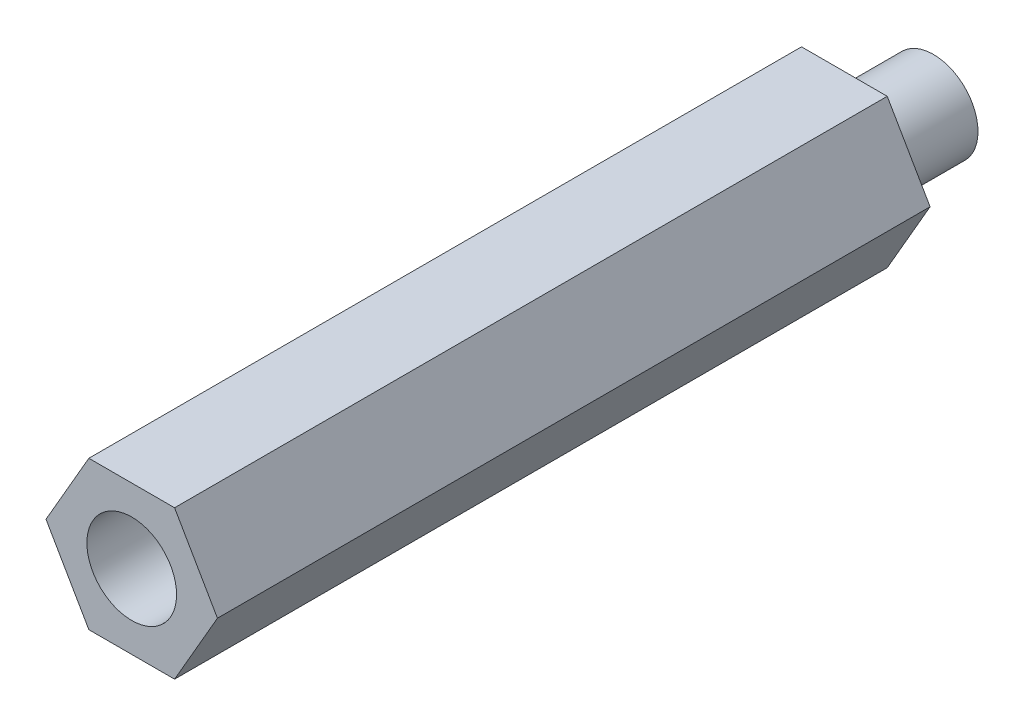
SolidWorks part; units mm, degrees
ref_plane "前视基准面" through (0, 0, 0) normal (0, 0, 1) x (1, 0, 0)
ref_plane "上视基准面" through (0, 0, 0) normal (0, 1, 0) x (1, 0, 0)
ref_plane "右视基准面" through (0, 0, 0) normal (1, 0, 0) x (0, 0, -1)
other "Configuration Table"
sketch "Female_M3_hex_standoff_AF5_Sketch" plane through (0, 0, 0) normal (0, 0, 1) x (1, 0, 0)
  line L0 (2.8868, 0) -> (1.4434, 2.5)
  line L1 (1.4434, 2.5) -> (-1.4434, 2.5)
  line L2 (-1.4434, 2.5) -> (-2.8868, 0)
  line L3 (-2.8868, 0) -> (-1.4434, -2.5)
  line L4 (-1.4434, -2.5) -> (1.4434, -2.5)
  line L5 (1.4434, -2.5) -> (2.8868, 0)
  circle A0 centre (0, 0) radius 1.51
extrude "Female_M3_hex_standoff_AF5" add sketch "Female_M3_hex_standoff_AF5_Sketch" along normal blind 24 separate body
sketch "Stud_root_Sketch" plane through (0, 0, 0) normal (0, 0, 1) x (1, 0, 0)
  circle A0 centre (0, 0) radius 1.85
extrude "Stud_root" add sketch "Stud_root_Sketch" along normal blind 0.45
sketch "Male_M3_stud_envelope_Sketch" plane through (0, 0, 0) normal (0, 0, 1) x (1, 0, 0)
  circle A0 centre (0, 0) radius 1.5
extrude "Male_M3_stud_envelope" add sketch "Male_M3_stud_envelope_Sketch" along normal blind 3 from offset 3
